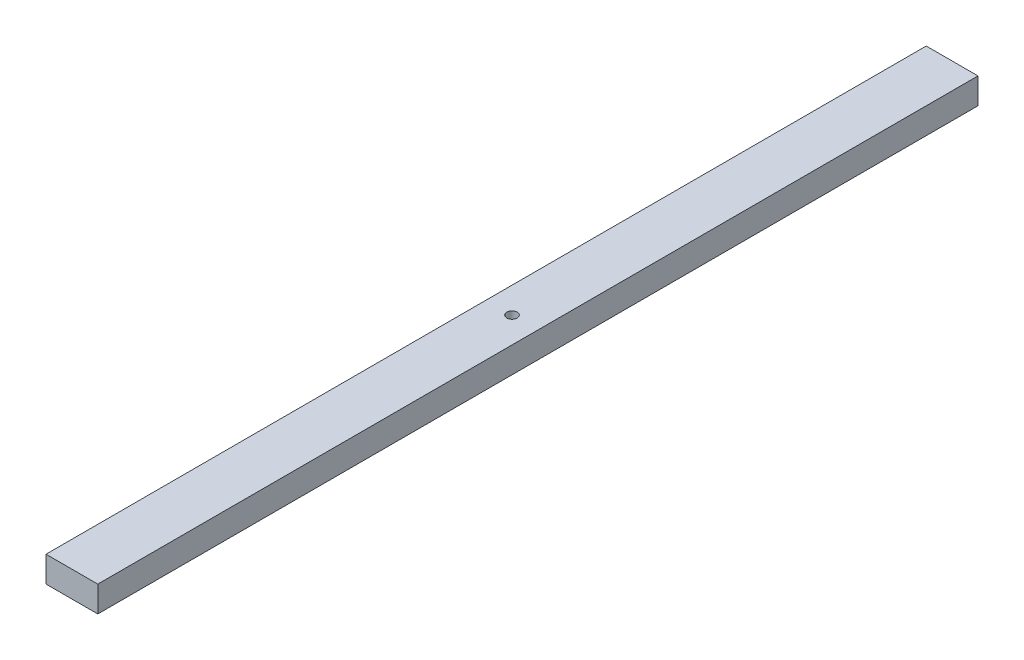
SolidWorks part; units mm, degrees
ref_plane "Front" through (0, 0, 0) normal (0, 0, 1) x (1, 0, 0)
ref_plane "Top" through (0, 0, 0) normal (0, 1, 0) x (1, 0, 0)
ref_plane "Right" through (0, 0, 0) normal (1, 0, 0) x (0, 0, -1)
sketch "Esquisse1" plane through (0, 0, 0) normal (0, 0, 1) x (1, 0, 0)
  line L1 (0, 0) -> (100, 0)
  line L2 (0, 0) -> (0, 50)
  line L3 (0, 50) -> (100, 50)
  line L4 (100, 0) -> (100, 50)
  dimension "D1" = 100
  dimension "D2" = 50
extrude "Boss.-Extru.1" add sketch "Esquisse1" along normal blind 1700
sketch "Esquisse2" plane through (0, 0, 0) normal (0, -1, 0) x (1, 0, 0)
  line L0 (50, 0) -> (50, 1700) construction
  line L1 (0, 0) -> (100, 0) construction
  line L2 (0, 1700) -> (100, 1700) construction
  circle A0 centre (50, 850) radius 10
  dimension "D1" = 20
extrude "Enlèv. mat.-Extru.1" cut sketch "Esquisse2" against normal through all
